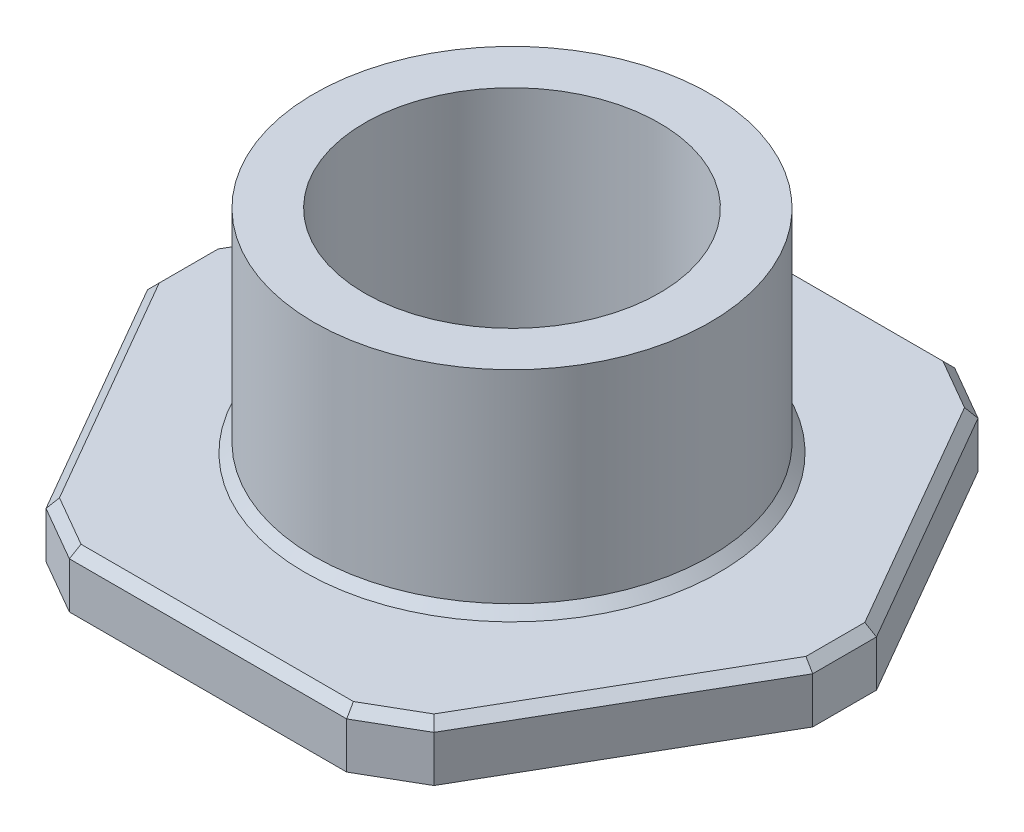
SolidWorks part; units mm, degrees
ref_plane "Front Plane" through (0, 0, 0) normal (0, 0, 1) x (1, 0, 0)
ref_plane "Top Plane" through (0, 0, 0) normal (0, 1, 0) x (1, 0, 0)
ref_plane "Right Plane" through (0, 0, 0) normal (1, 0, 0) x (0, 0, -1)
sketch "Sketch1" plane through (0, 0, 0) normal (0, 1, 0) x (1, 0, 0)
  line L0 (0, 0) -> (38.1051, 0) construction
  line L1 (38.1051, 0) -> (19.0526, 33)
  line L2 (19.0526, 33) -> (-19.0526, 33)
  line L3 (-19.0526, 33) -> (-38.1051, 0)
  line L4 (-38.1051, 0) -> (-19.0526, -33)
  line L5 (-19.0526, -33) -> (19.0526, -33)
  line L6 (19.0526, -33) -> (38.1051, 0)
  circle A0 centre (0, 0) radius 16
  circle A1 centre (0, 0) radius 33 construction
  dimension "D1" = 32
  dimension "D2" = 66
extrude "Boss-Extrude1" add sketch "Sketch1" along normal blind 6
sketch "Sketch2" plane through (0, 6, 0) normal (0, 1, 0) x (1, 0, 0)
  circle A0 centre (0, 0) radius 16
  circle A1 centre (0, 0) radius 21.5
  circle A2 centre (0, 0) radius 16 construction
  dimension "D1" = 43
extrude "Boss-Extrude2" add sketch "Sketch2" along normal blind 23
chamfer "Chamfer1" distance 4 6 edges at (-19.0526, 3, -33) (-38.1051, 3, 0) (-19.0526, 3, 33) (19.0526, 3, 33) (38.1051, 3, 0) (19.0526, 3, -33)
chamfer "Chamfer3" distance 1 angle 45 13 edges at (0, 6, 21.5) (-18.0526, 6, -31.2679) (0, 6, -33) (18.0526, 6, -31.2679) (28.5788, 6, -16.5) (36.1051, 6, 0) (28.5788, 6, 16.5) (18.0526, 6, 31.2679) (0, 6, 33) (-18.0526, 6, 31.2679) (-28.5788, 6, 16.5) (-36.1051, 6, 0) (-28.5788, 6, -16.5)
